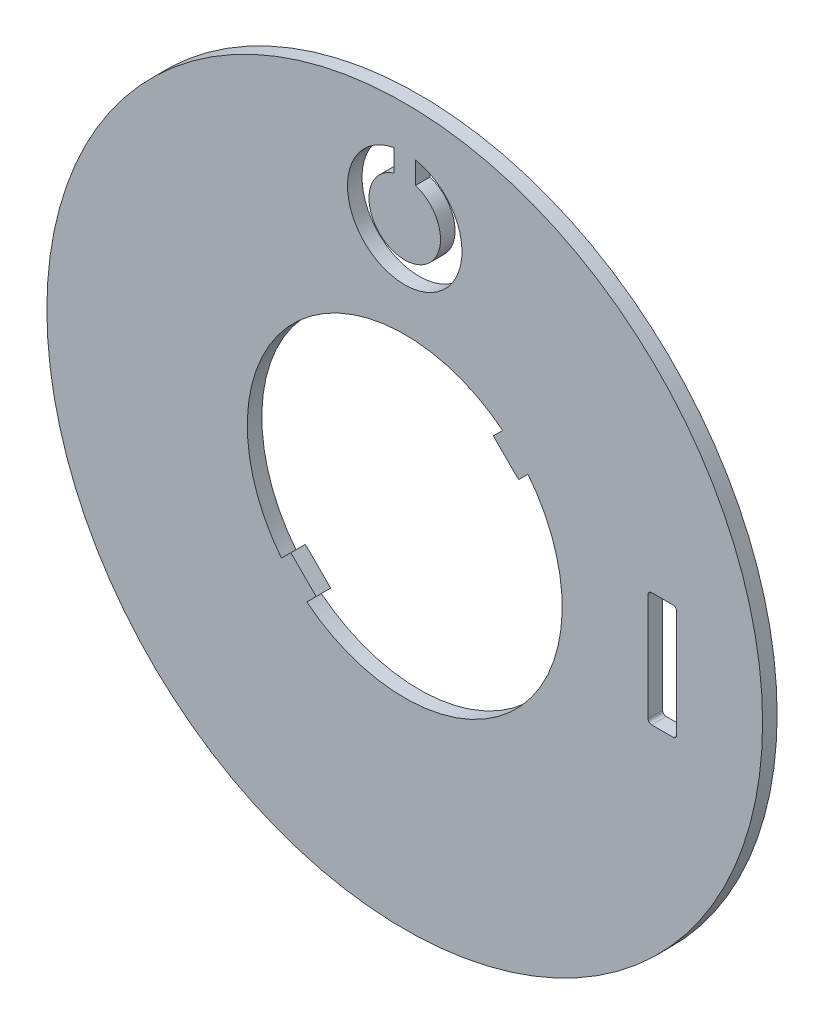
SolidWorks part; units mm, degrees
material "6061-T4 (SS)"
ref_plane "Front Plane" through (0, 0, 0) normal (0, 0, 1) x (1, 0, 0)
ref_plane "Top Plane" through (0, 0, 0) normal (0, 1, 0) x (1, 0, 0)
ref_plane "Right Plane" through (0, 0, 0) normal (1, 0, 0) x (0, 0, -1)
sketch "Sketch1" plane through (0, 0, 0) normal (0, 0, 1) x (1, 0, 0)
  line L4 (115.6621, 68.6943) -> (113.8943, 70.4621)
  line L5 (114.955, 67.9872) -> (115.6621, 68.6943)
  line L6 (113.1872, 69.755) -> (114.955, 67.9872)
  line L7 (113.8943, 70.4621) -> (113.1872, 69.755)
  line L8 (115.6621, 68.6943) -> (113.8943, 70.4621)
  line L9 (114.955, 67.9872) -> (115.6621, 68.6943)
  line L10 (113.1872, 69.755) -> (114.955, 67.9872)
  line L11 (113.8943, 70.4621) -> (113.1872, 69.755)
  line L12 (-125.42, 34.7291) -> (-68.36, 34.7291)
  line L13 (-68.36, 34.7291) -> (-68.36, 51.7891)
  line L14 (-68.36, 51.7891) -> (-125.42, 51.7891)
  line L15 (-125.42, 51.7891) -> (-125.42, 34.7291)
  line L16 (-125.42, 34.7291) -> (-68.36, 34.7291)
  line L17 (-68.36, 34.7291) -> (-68.36, 51.7891)
  line L18 (-68.36, 51.7891) -> (-125.42, 51.7891)
  line L19 (-125.42, 51.7891) -> (-125.42, 34.7291)
  line L20 (100.1057, 53.1379) -> (100.8128, 53.845)
  line L21 (100.8128, 53.845) -> (99.045, 55.6128)
  line L22 (99.045, 55.6128) -> (98.3379, 54.9057)
  line L23 (98.3379, 54.9057) -> (100.1057, 53.1379)
  line L24 (100.1057, 53.1379) -> (100.8128, 53.845)
  line L25 (100.8128, 53.845) -> (99.045, 55.6128)
  line L26 (99.045, 55.6128) -> (98.3379, 54.9057)
  line L27 (98.3379, 54.9057) -> (100.1057, 53.1379)
  line L28 (45.6621, 68.6943) -> (43.8943, 70.4621)
  line L29 (44.955, 67.9872) -> (45.6621, 68.6943)
  line L30 (43.1872, 69.755) -> (44.955, 67.9872)
  line L31 (43.8943, 70.4621) -> (43.1872, 69.755)
  line L32 (45.6621, 68.6943) -> (43.8943, 70.4621)
  line L33 (44.955, 67.9872) -> (45.6621, 68.6943)
  line L34 (43.1872, 69.755) -> (44.955, 67.9872)
  line L35 (43.8943, 70.4621) -> (43.1872, 69.755)
  line L36 (30.1057, 53.1379) -> (30.8128, 53.845)
  line L37 (28.3379, 54.9057) -> (30.1057, 53.1379)
  line L38 (29.045, 55.6128) -> (28.3379, 54.9057)
  line L39 (30.8128, 53.845) -> (29.045, 55.6128)
  line L40 (30.1057, 53.1379) -> (30.8128, 53.845)
  line L41 (28.3379, 54.9057) -> (30.1057, 53.1379)
  line L42 (29.045, 55.6128) -> (28.3379, 54.9057)
  line L43 (30.8128, 53.845) -> (29.045, 55.6128)
  circle A3 centre (-76.89, 43.2591) radius 6.03
  circle A5 centre (-76.89, 43.2591) radius 6.03
  circle A7 centre (-96.89, 43.2591) radius 6.03
  circle A9 centre (-96.89, 43.2591) radius 6.03
  circle A11 centre (-116.89, 43.2591) radius 6.03
  circle A13 centre (-116.89, 43.2591) radius 6.03
  circle A28 centre (37, 61.8) radius 25
  circle A29 centre (37, 61.8) radius 25
  circle A30 centre (107, 61.8) radius 25
  circle A31 centre (107, 61.8) radius 25
  circle A32 centre (37, 61.8) radius 11
  circle A33 centre (37, 61.8) radius 11
  circle A34 centre (107, 61.8) radius 11
  circle A35 centre (107, 61.8) radius 11
  dimension "D1" = 0
  dimension "D2" = 0
  dimension "D3" = 0
  dimension "D4" = 0
  dimension "D5" = 0
  dimension "D6" = 0
  dimension "D7" = 0
  dimension "D8" = 0
  dimension "D9" = 0
  dimension "D10" = 0
  dimension "D11" = 0
  dimension "D12" = 0
extrude "Boss-Extrude1" add sketch "Sketch1" along normal blind 1.016 contours A31 A35 L11 L8 L9 L24 L27 L26
sketch "Sketch2" plane through (0, 0, 0) normal (0, 0, 1) x (1, 0, 0)
  line L0 (107, 72.8) -> (107, 86.8) construction
  line L1 (106.25, 82.1848) -> (106.25, 83.7291)
  line L2 (107.75, 83.7291) -> (107.75, 82.1848)
  line L3 (107.75, 82.957) -> (106.25, 82.957) construction
  line L7 (118, 61.8) -> (132, 61.8) construction
  line L8 (124.25, 57.8) -> (125.75, 57.8)
  line L9 (124, 58.05) -> (124, 65.55)
  line L10 (124.25, 65.8) -> (125.75, 65.8)
  line L11 (126, 58.05) -> (126, 65.55)
  line L12 (124, 57.8) -> (126, 65.8) construction
  line L13 (124, 65.8) -> (126, 57.8) construction
  circle A0 centre (107, 61.8) radius 25 construction
  arc A6 (106.25, 83.7291) -> (107.75, 83.7291) centre (107, 79.8) ccw
  arc A7 (106.25, 82.1848) -> (107.75, 82.1848) centre (107, 79.8) ccw
  arc A11 (124.25, 57.8) -> (124, 58.05) centre (124.25, 58.05) cw
  arc A12 (125.75, 57.8) -> (126, 58.05) centre (125.75, 58.05) ccw
  arc A13 (125.75, 65.8) -> (126, 65.55) centre (125.75, 65.55) cw
  arc A14 (124, 65.55) -> (124.25, 65.8) centre (124.25, 65.55) cw
  circle A15 centre (107, 61.8) radius 11 construction
  circle A16 centre (107, 61.8) radius 25
  circle A17 centre (107, 61.8) radius 11
  point P1 (125, 61.8)
  dimension "D3" = 4
  dimension "D7" = 0.25
  dimension "D2" = 1.5
  dimension "D4" = 2
  dimension "D5" = 8
  dimension "D6" = 1.5
extrude "Cut-Extrude1" cut sketch "Sketch2" along normal through all contours A7 L1 A6 L2 | A14 L9 A11 L8 A12 L11 A13 L10
